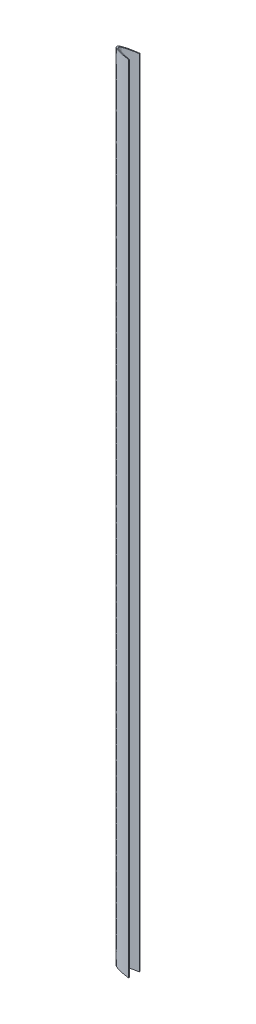
SolidWorks part; units mm, degrees
material "C-Glass Fiber"
ref_plane "Front Plane" through (0, 0, 0) normal (0, 0, 1) x (1, 0, 0)
ref_plane "Top Plane" through (0, 0, 0) normal (0, 1, 0) x (1, 0, 0)
ref_plane "Right Plane" through (0, 0, 0) normal (1, 0, 0) x (0, 0, -1)
sketch "Sketch1" plane through (0, 0, 0) normal (0, 1, 0) x (1, 0, 0)
  line L0 (8.6497, 0) -> (159.6497, 0) construction
  line L1 (199.516, 0) -> (0, 0) construction
  line L2 (18.402, 0.8986) -> (27.2015, 0.8986) construction
  line L3 (174.516, -4) -> (174.516, 4)
  line L4 (0, 0) -> (3, 0) construction
  line L5 (174.516, 4) -> (162.1151, 4)
  line L6 (162.1151, 0) -> (162.1151, 4)
  line L7 (162.1151, 4) -> (159.3811, 4)
  line L8 (174.516, -4) -> (162.1151, -4)
  line L9 (199.516, 0) -> (174.516, 0) construction
  line L10 (162.1151, -4) -> (159.3811, -4)
  line L11 (167.5772, 4) -> (164.4102, 7.167)
  line L12 (167.5772, -4) -> (164.4102, -7.167)
  line L13 (14.3352, 4.334) -> (13.9611, 5.1543)
  line L14 (14.3352, -4.334) -> (13.9611, -5.1543)
  line L15 (89.1955, -13.0378) -> (89.1955, 13.0378)
  line L16 (157.3717, 1.4283) -> (158.2891, 0.8986)
  line L17 (158.2891, -0.8986) -> (157.3717, -1.4283)
  line L18 (19.3194, -1.4283) -> (18.402, -0.8986)
  line L19 (87.4955, 13.0378) -> (87.4955, -13.0378)
  line L20 (18.402, 0.8986) -> (19.3194, 1.4283)
  line L21 (27.2015, 0.8986) -> (27.2015, 9.5398) construction
  line L22 (27.2015, 9.5398) -> (27.7748, 7.3709) construction
  line L23 (52.8504, 10.8491) -> (52.4694, 14.0253) construction
  line L24 (52.4694, 14.0253) -> (52.6599, 12.4372) construction
  line L25 (52.6599, 12.4372) -> (52.6599, -10.8199) construction
  line L26 (52.6599, -12.5396) -> (52.8504, -10.8491) construction
  line L27 (52.8504, -10.8491) -> (52.4694, -14.0253) construction
  line L28 (52.6599, -12.5396) -> (52.4694, -14.0253)
  line L29 (52.4694, 14.0253) -> (52.6478, 12.5378)
  arc A14 (89.6984, 13.5378) -> (89.1955, 13.0378) centre (89.6955, 13.0378) ccw
  arc A15 (157.2309, 3.2326) -> (89.6984, 13.5378) centre (88.3455, -221.7583) ccw
  arc A16 (157.4385, 2.4013) -> (157.2309, 3.2326) centre (157.0846, 2.7545) ccw
  arc A17 (157.4385, 2.4013) -> (157.2382, 2.1822) centre (159.8455, 0) ccw
  arc A18 (157.2382, 2.1822) -> (157.3717, 1.4283) centre (157.6217, 1.8613) ccw
  arc A19 (158.2891, 0.8986) -> (158.4228, 0.9305) centre (158.3391, 0.9852) ccw
  arc A20 (158.4228, -0.9305) -> (158.4228, 0.9305) centre (159.8455, 0) ccw
  arc A21 (158.4228, -0.9305) -> (158.2891, -0.8986) centre (158.3391, -0.9852) ccw
  arc A22 (157.3717, -1.4283) -> (157.2382, -2.1822) centre (157.6217, -1.8613) ccw
  arc A23 (157.2382, -2.1822) -> (157.4385, -2.4013) centre (159.8455, 0) ccw
  arc A24 (157.2309, -3.2326) -> (157.4385, -2.4013) centre (157.0846, -2.7545) ccw
  arc A25 (89.6984, -13.5378) -> (157.2309, -3.2326) centre (88.3455, 221.7583) ccw
  arc A26 (89.1955, -13.0378) -> (89.6984, -13.5378) centre (89.6955, -13.0378) ccw
  arc A27 (18.2683, 0.9305) -> (18.2683, -0.9305) centre (16.8455, 0) ccw
  arc A28 (18.402, -0.8986) -> (18.2683, -0.9305) centre (18.352, -0.9852) ccw
  arc A29 (19.4528, -2.1822) -> (19.3194, -1.4283) centre (19.0694, -1.8613) ccw
  arc A30 (19.2525, -2.4013) -> (19.4528, -2.1822) centre (16.8455, 0) ccw
  arc A31 (19.2525, -2.4013) -> (19.4601, -3.2326) centre (19.6065, -2.7545) ccw
  arc A32 (19.4601, -3.2326) -> (86.9927, -13.5378) centre (88.3455, 221.7583) ccw
  arc A33 (86.9927, -13.5378) -> (87.4955, -13.0378) centre (86.9955, -13.0378) ccw
  arc A34 (87.4955, 13.0378) -> (86.9927, 13.5378) centre (86.9955, 13.0378) ccw
  arc A35 (86.9927, 13.5378) -> (19.4601, 3.2326) centre (88.3455, -221.7583) ccw
  arc A36 (19.4601, 3.2326) -> (19.2525, 2.4013) centre (19.6065, 2.7545) ccw
  arc A37 (19.4528, 2.1822) -> (19.2525, 2.4013) centre (16.8455, 0) ccw
  arc A38 (19.3194, 1.4283) -> (19.4528, 2.1822) centre (19.0694, 1.8613) ccw
  arc A39 (18.2683, 0.9305) -> (18.402, 0.8986) centre (18.352, 0.9852) ccw
  arc A40 (15.6181, 3.807) -> (15.6181, -3.807) centre (16.8455, 0) ccw
  arc A41 (15.6181, -3.807) -> (161.073, -3.807) centre (88.3455, 221.7583) ccw
  arc A42 (161.073, -3.807) -> (161.073, 3.807) centre (159.8455, 0) ccw
  arc A43 (161.073, 3.807) -> (15.6181, 3.807) centre (88.3455, -221.7583) ccw
  spline S0 degree 3 poles (197.109, -0.2051) (200.1208, 0) (197.1087, 0.2051) (194.6531, 0.5762) (189.72, 1.1908) (184.6864, 2.2149) (178.002, 3.7758) (169.5801, 5.8337) (159.6184, 8.401) (149.6599, 10.9028) (139.6938, 13.2101) (129.7249, 15.1876) (119.7492, 16.7362) (109.7441, 17.477) (99.7623, 17.8926) (89.7817, 17.9957) (79.8024, 17.8387) (69.8227, 17.405) (59.8429, 16.697) (49.8607, 15.7095) (39.8749, 14.3992) (29.8779, 12.7127) (21.5647, 10.875) (14.9303, 9.0318) (9.9047, 7.4074) (5.7328, 5.7018) (2.9121, 4.2307) (1.6214, 3.2706) (0.808, 2.4827) (0.1659, 1.4447) (-0.0829, -0.0002) (0.1659, -1.4451) (0.8081, -2.4831) (1.6215, -3.2709) (2.9121, -4.231) (5.7328, -5.7022) (9.9048, -7.4078) (14.9304, -9.0321) (21.5647, -10.8753) (29.8779, -12.713) (39.875, -14.3995) (49.8607, -15.7097) (59.8429, -16.6972) (69.8228, -17.4053) (79.8024, -17.8389) (89.7818, -17.9959) (99.7623, -17.8928) (109.7441, -17.4771) (119.7492, -16.7363) (129.7249, -15.1877) (139.6939, -13.2102) (149.6599, -10.9028) (159.6186, -8.4014) (167.9931, -6.2416) (174.6383, -4.5998) (181.3078, -3.0002) (187.7797, -1.4397) (194.6469, -0.5761) (197.109, -0.2051) (200.1208, 0) (197.1087, 0.2051) knots -0.02448 -0.010984 -0.00276 0 0.00276 0.010984 0.02448 0.035911 0.049305 0.074294 0.099343 0.12436 0.149265 0.17401 0.198547 0.222904 0.247201 0.271478 0.295756 0.320055 0.344391 0.368787 0.393273 0.417901 0.442781 0.455382 0.46816 0.481314 0.488256 0.491308 0.493017 0.496509 0.500002 0.503494 0.506986 0.508696 0.511748 0.518689 0.531843 0.544621 0.557222 0.582102 0.60673 0.631216 0.655612 0.679949 0.704247 0.728526 0.752803 0.777099 0.801456 0.825994 0.850739 0.875644 0.90066 0.925709 0.938747 0.950698 0.97552 0.989016 0.99724 1 1.00276 1.010984 1.02448 only from (199.516, 0) to (199.516, 0)
  spline S1 degree 3 poles (187.2347, -0.1858) (189.9635, 0) (187.2344, 0.1858) (185.0096, 0.522) (180.5401, 1.0789) (175.9796, 2.0068) (169.9234, 3.421) (162.293, 5.2855) (153.2674, 7.6115) (144.2448, 9.8782) (135.2153, 11.9687) (126.1833, 13.7604) (117.1451, 15.1634) (108.0803, 15.8346) (99.0365, 16.2111) (89.9939, 16.3046) (80.9524, 16.1624) (71.9106, 15.7694) (62.8686, 15.128) (53.8246, 14.2332) (44.7773, 13.0461) (35.7197, 11.5181) (28.1878, 9.8531) (22.1769, 8.1831) (17.6236, 6.7114) (13.8437, 5.1661) (11.2881, 3.8333) (10.1188, 2.9634) (9.3818, 2.2496) (8.8, 1.3091) (8.5746, 0) (8.8, -1.3091) (9.3818, -2.2496) (10.1188, -2.9634) (11.2881, -3.8333) (13.8437, -5.1661) (17.6236, -6.7114) (22.1769, -8.1831) (28.1878, -9.8531) (35.7197, -11.5181) (44.7773, -13.0461) (53.8246, -14.2332) (62.8686, -15.128) (71.9106, -15.7694) (80.9524, -16.1624) (89.9939, -16.3046) (99.0365, -16.2111) (108.0803, -15.8346) (117.1451, -15.1634) (126.1833, -13.7604) (135.2154, -11.9687) (144.2448, -9.8781) (153.2676, -7.6118) (160.8551, -5.655) (166.8758, -4.1675) (172.9185, -2.7183) (178.7822, -1.3044) (185.004, -0.5219) (187.2347, -0.1858) (189.9635, 0) (187.2344, 0.1858) knots -0.02448 -0.010984 -0.00276 0 0.00276 0.010984 0.02448 0.035911 0.049305 0.074294 0.099343 0.12436 0.149265 0.17401 0.198547 0.222904 0.247201 0.271478 0.295756 0.320055 0.344391 0.368787 0.393273 0.417901 0.442781 0.455382 0.46816 0.481314 0.488256 0.491308 0.493017 0.496509 0.500002 0.503494 0.506986 0.508696 0.511748 0.518689 0.531843 0.544621 0.557222 0.582102 0.60673 0.631216 0.655612 0.679949 0.704247 0.728526 0.752803 0.777099 0.801456 0.825994 0.850739 0.875644 0.90066 0.925709 0.938747 0.950698 0.97552 0.989016 0.99724 1 1.00276 1.010984 1.02448 only from (189.4155, 0) to (189.4155, 0)
  spline S6 degree 3 poles (153.5408, -41.5497) (156.2695, -41.3639) (153.5405, -41.1781) (151.3157, -40.8419) (146.8462, -40.285) (142.2856, -39.3571) (136.2295, -37.9429) (128.599, -36.0784) (119.5735, -33.7524) (110.5509, -31.4857) (101.5214, -29.3952) (92.4893, -27.6035) (83.4511, -26.2005) (74.3863, -25.5293) (65.3425, -25.1527) (56.3, -25.0593) (47.2585, -25.2015) (38.2167, -25.5944) (29.1747, -26.2359) (20.1306, -27.1306) (11.0833, -28.3178) (2.0258, -29.8457) (-5.5061, -31.5108) (-11.517, -33.1808) (-16.0703, -34.6524) (-19.8502, -36.1977) (-22.4058, -37.5306) (-23.5752, -38.4005) (-24.3121, -39.1143) (-24.8939, -40.0548) (-25.1194, -41.3639) (-24.8939, -42.673) (-24.3121, -43.6134) (-23.5752, -44.3272) (-22.4058, -45.1971) (-19.8502, -46.53) (-16.0703, -48.0753) (-11.517, -49.547) (-5.5061, -51.217) (2.0258, -52.882) (11.0833, -54.41) (20.1306, -55.5971) (29.1747, -56.4918) (38.2167, -57.1333) (47.2585, -57.5262) (56.3, -57.6684) (65.3425, -57.575) (74.3863, -57.1985) (83.4511, -56.5273) (92.4893, -55.1242) (101.5214, -53.3326) (110.5508, -51.242) (119.5737, -48.9757) (127.1611, -47.0189) (133.1818, -45.5314) (139.2245, -44.0821) (145.0882, -42.6682) (151.3101, -41.8858) (153.5408, -41.5497) (156.2695, -41.3639) (153.5405, -41.1781) knots -0.02448 -0.010984 -0.00276 0 0.00276 0.010984 0.02448 0.035911 0.049305 0.074294 0.099343 0.12436 0.149265 0.17401 0.198547 0.222904 0.247201 0.271478 0.295756 0.320055 0.344391 0.368787 0.393273 0.417901 0.442781 0.455382 0.46816 0.481314 0.488256 0.491308 0.493017 0.496509 0.500002 0.503494 0.506986 0.508696 0.511748 0.518689 0.531843 0.544621 0.557222 0.582102 0.60673 0.631216 0.655612 0.679949 0.704247 0.728526 0.752803 0.777099 0.801456 0.825994 0.850739 0.875644 0.90066 0.925709 0.938747 0.950698 0.97552 0.989016 0.99724 1 1.00276 1.010984 1.02448 only from (155.7216, -41.3639) to (155.7216, -41.3639)
  spline S7 degree 3 poles (163.5385, -41.569) (166.5502, -41.3639) (163.5381, -41.1588) (161.0825, -40.7877) (156.1494, -40.1731) (151.1158, -39.149) (144.4315, -37.5881) (136.0096, -35.5301) (126.0478, -32.9629) (116.0894, -30.4611) (106.1233, -28.1538) (96.1543, -26.1762) (86.1786, -24.6277) (76.1735, -23.8869) (66.1917, -23.4713) (56.2112, -23.3682) (46.2318, -23.5251) (36.2522, -23.9588) (26.2723, -24.6669) (16.2901, -25.6544) (6.3044, -26.9647) (-3.6927, -28.6511) (-12.0058, -30.4889) (-18.6402, -32.3321) (-23.6658, -33.9564) (-27.8378, -35.662) (-30.6585, -37.1332) (-31.9491, -38.0933) (-32.7625, -38.8811) (-33.4047, -39.9191) (-33.6535, -41.364) (-33.4047, -42.8089) (-32.7625, -43.8469) (-31.9491, -44.6348) (-30.6585, -45.5949) (-27.8378, -47.066) (-23.6658, -48.7716) (-18.6402, -50.3959) (-12.0058, -52.2392) (-3.6926, -54.0769) (6.3044, -55.7633) (16.2901, -57.0736) (26.2723, -58.0611) (36.2522, -58.7691) (46.2318, -59.2028) (56.2112, -59.3597) (66.1917, -59.2566) (76.1736, -58.841) (86.1787, -58.1002) (96.1543, -56.5516) (106.1233, -54.5741) (116.0893, -52.2667) (126.0481, -49.7652) (134.4225, -47.6055) (141.0677, -45.9637) (147.7372, -44.3641) (154.2092, -42.8035) (161.0764, -41.94) (163.5385, -41.569) (166.5502, -41.3639) (163.5381, -41.1588) knots -0.02448 -0.010984 -0.00276 0 0.00276 0.010984 0.02448 0.035911 0.049305 0.074294 0.099343 0.12436 0.149265 0.17401 0.198547 0.222904 0.247201 0.271478 0.295756 0.320055 0.344391 0.368787 0.393273 0.417901 0.442781 0.455382 0.46816 0.481314 0.488256 0.491308 0.493017 0.496509 0.500002 0.503494 0.506986 0.508696 0.511748 0.518689 0.531843 0.544621 0.557222 0.582102 0.60673 0.631216 0.655612 0.679949 0.704247 0.728526 0.752803 0.777099 0.801456 0.825994 0.850739 0.875644 0.90066 0.925709 0.938747 0.950698 0.97552 0.989016 0.99724 1 1.00276 1.010984 1.02448 only from (165.9455, -41.3639) to (165.9455, -41.3639)
extrude "Boss-Extrude1" add sketch "Sketch1" along normal blind 2000
